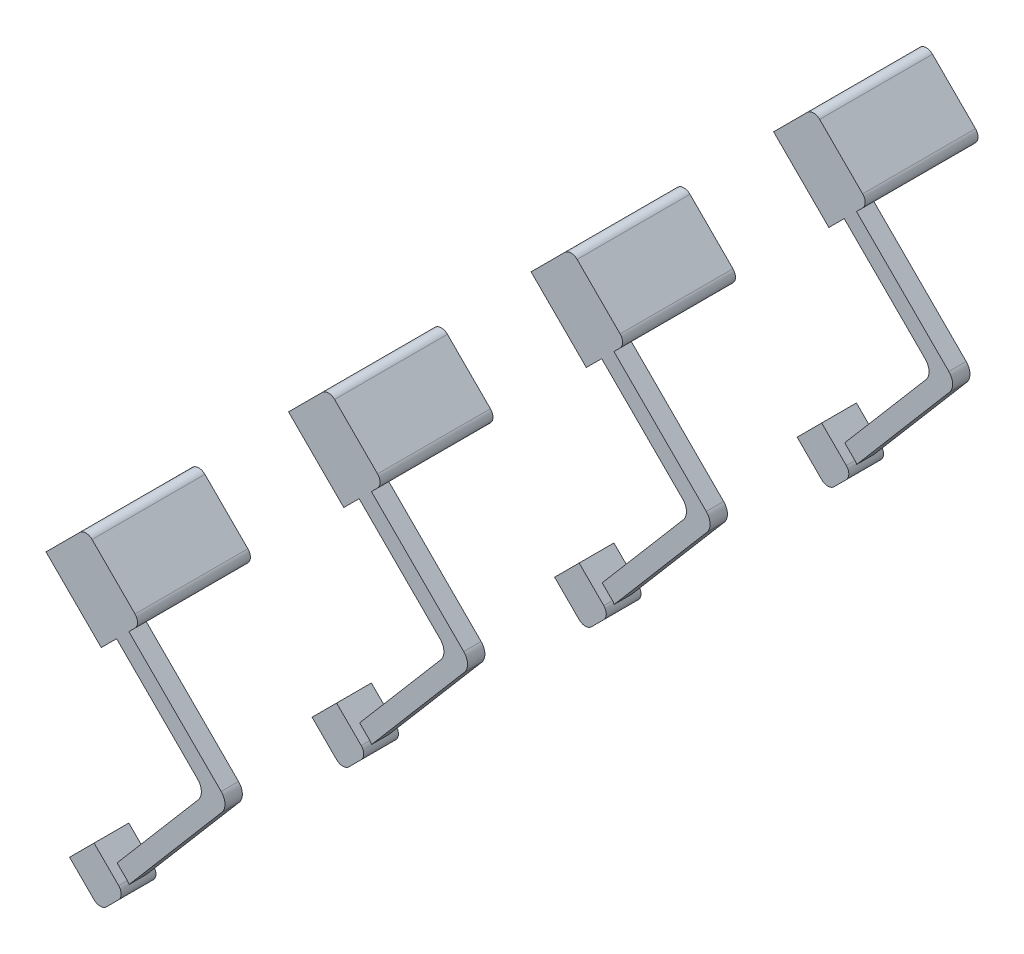
SolidWorks part; units mm, degrees
ref_plane "Front Plane" through (0, 0, 0) normal (0, 0, 1) x (1, 0, 0)
ref_plane "Top Plane" through (0, 0, 0) normal (0, 1, 0) x (1, 0, 0)
ref_plane "Right Plane" through (0, 0, 0) normal (1, 0, 0) x (0, 0, -1)
other "Configuration Table"
sketch "Sketch1" plane through (0, 0, 0) normal (0, 0, 1) x (1, 0, 0)
  line L0 (261.5942, 287.05) -> (287.05, 261.5942)
  line L1 (287.05, 261.5942) -> (302.6063, 277.1505)
  line L2 (302.6063, 282.8074) -> (282.8074, 302.6063)
  line L3 (277.1505, 302.6063) -> (261.5942, 287.05)
  arc A0 (302.6063, 277.1505) -> (302.6063, 282.8074) centre (299.7779, 279.9789) ccw
  arc A1 (282.8074, 302.6063) -> (277.1505, 302.6063) centre (279.9789, 299.7779) ccw
extrude "Coil 1" add sketch "Sketch1" along normal blind 52 from offset 4.1
sketch "Sketch2" plane through (0, 0, 0) normal (0, 0, 1) x (1, 0, 0)
  line L0 (288.4642, 274.3221) -> (331.4337, 231.3526)
  line L1 (331.7585, 223.2191) -> (288.9548, 172.9712)
  line L2 (288.9548, 172.9712) -> (295.0447, 167.7835)
  line L3 (295.0447, 167.7835) -> (342.6378, 223.6536)
  line L4 (342.3129, 231.7871) -> (294.1211, 279.9789)
  line L5 (294.1211, 279.9789) -> (288.4642, 274.3221)
  arc A0 (331.4337, 231.3526) -> (331.7585, 223.2191) centre (327.1911, 227.1099) cw
  arc A1 (342.6378, 223.6536) -> (342.3129, 231.7871) centre (338.0703, 227.5444) ccw
extrude "Plug Lead 1" add sketch "Sketch2" along normal blind 8 from offset 39.9
sketch "Sketch3" plane through (0, 0, 0) normal (0, 0, 1) x (1, 0, 0)
  line L0 (276.4434, 174.62) -> (287.7571, 163.3063)
  line L1 (293.414, 163.3063) -> (299.0708, 168.9632)
  line L2 (299.0708, 174.62) -> (287.7571, 185.9337)
  line L3 (287.7571, 185.9337) -> (276.4434, 174.62)
  arc A0 (287.7571, 163.3063) -> (293.414, 163.3063) centre (290.5855, 166.1347) ccw
  arc A1 (299.0708, 168.9632) -> (299.0708, 174.62) centre (296.2424, 171.7916) ccw
extrude "Plug Boot 1" add sketch "Sketch3" along normal blind 16 from offset 35.9
sketch "Sketch4" plane through (0, 0, 0) normal (0, 0, 1) x (1, 0, 0)
  line L0 (261.5942, 287.05) -> (287.05, 261.5942)
  line L1 (287.05, 261.5942) -> (302.6063, 277.1505)
  line L2 (302.6063, 282.8074) -> (282.8074, 302.6063)
  line L3 (277.1505, 302.6063) -> (261.5942, 287.05)
  arc A0 (302.6063, 277.1505) -> (302.6063, 282.8074) centre (299.7779, 279.9789) ccw
  arc A1 (282.8074, 302.6063) -> (277.1505, 302.6063) centre (279.9789, 299.7779) ccw
extrude "Coil 3" add sketch "Sketch4" along normal blind 52 from offset 115.86
sketch "Sketch5" plane through (0, 0, 0) normal (0, 0, 1) x (1, 0, 0)
  line L0 (288.4642, 274.3221) -> (331.4337, 231.3526)
  line L1 (331.7585, 223.2191) -> (288.9548, 172.9712)
  line L2 (288.9548, 172.9712) -> (295.0447, 167.7835)
  line L3 (295.0447, 167.7835) -> (342.6378, 223.6536)
  line L4 (342.3129, 231.7871) -> (294.1211, 279.9789)
  line L5 (294.1211, 279.9789) -> (288.4642, 274.3221)
  arc A0 (331.4337, 231.3526) -> (331.7585, 223.2191) centre (327.1911, 227.1099) cw
  arc A1 (342.6378, 223.6536) -> (342.3129, 231.7871) centre (338.0703, 227.5444) ccw
extrude "Plug Lead 3" add sketch "Sketch5" along normal blind 8 from offset 71.86
sketch "Sketch6" plane through (0, 0, 0) normal (0, 0, 1) x (1, 0, 0)
  line L0 (276.4434, 174.62) -> (287.7571, 163.3063)
  line L1 (293.414, 163.3063) -> (299.0708, 168.9632)
  line L2 (299.0708, 174.62) -> (287.7571, 185.9337)
  line L3 (287.7571, 185.9337) -> (276.4434, 174.62)
  arc A0 (287.7571, 163.3063) -> (293.414, 163.3063) centre (290.5855, 166.1347) ccw
  arc A1 (299.0708, 168.9632) -> (299.0708, 174.62) centre (296.2424, 171.7916) ccw
extrude "Plug Boot 3" add sketch "Sketch6" along normal blind 16 from offset 75.86
sketch "Sketch7" plane through (0, 0, 0) normal (0, 0, 1) x (1, 0, 0)
  line L0 (261.5942, 287.05) -> (287.05, 261.5942)
  line L1 (287.05, 261.5942) -> (302.6063, 277.1505)
  line L2 (302.6063, 282.8074) -> (282.8074, 302.6063)
  line L3 (277.1505, 302.6063) -> (261.5942, 287.05)
  arc A0 (302.6063, 277.1505) -> (302.6063, 282.8074) centre (299.7779, 279.9789) ccw
  arc A1 (282.8074, 302.6063) -> (277.1505, 302.6063) centre (279.9789, 299.7779) ccw
extrude "Coil 5" add sketch "Sketch7" along normal blind 52 from offset 227.62
sketch "Sketch8" plane through (0, 0, 0) normal (0, 0, 1) x (1, 0, 0)
  line L0 (288.4642, 274.3221) -> (331.4337, 231.3526)
  line L1 (331.7585, 223.2191) -> (288.9548, 172.9712)
  line L2 (288.9548, 172.9712) -> (295.0447, 167.7835)
  line L3 (295.0447, 167.7835) -> (342.6378, 223.6536)
  line L4 (342.3129, 231.7871) -> (294.1211, 279.9789)
  line L5 (294.1211, 279.9789) -> (288.4642, 274.3221)
  arc A0 (331.4337, 231.3526) -> (331.7585, 223.2191) centre (327.1911, 227.1099) cw
  arc A1 (342.6378, 223.6536) -> (342.3129, 231.7871) centre (338.0703, 227.5444) ccw
extrude "Plug Lead 5" add sketch "Sketch8" along normal blind 8 from offset 183.62
sketch "Sketch9" plane through (0, 0, 0) normal (0, 0, 1) x (1, 0, 0)
  line L0 (276.4434, 174.62) -> (287.7571, 163.3063)
  line L1 (293.414, 163.3063) -> (299.0708, 168.9632)
  line L2 (299.0708, 174.62) -> (287.7571, 185.9337)
  line L3 (287.7571, 185.9337) -> (276.4434, 174.62)
  arc A0 (287.7571, 163.3063) -> (293.414, 163.3063) centre (290.5855, 166.1347) ccw
  arc A1 (299.0708, 168.9632) -> (299.0708, 174.62) centre (296.2424, 171.7916) ccw
extrude "Plug Boot 5" add sketch "Sketch9" along normal blind 16 from offset 187.62
sketch "Sketch10" plane through (0, 0, 0) normal (0, 0, 1) x (1, 0, 0)
  line L0 (261.5942, 287.05) -> (287.05, 261.5942)
  line L1 (287.05, 261.5942) -> (302.6063, 277.1505)
  line L2 (302.6063, 282.8074) -> (282.8074, 302.6063)
  line L3 (277.1505, 302.6063) -> (261.5942, 287.05)
  arc A0 (302.6063, 277.1505) -> (302.6063, 282.8074) centre (299.7779, 279.9789) ccw
  arc A1 (282.8074, 302.6063) -> (277.1505, 302.6063) centre (279.9789, 299.7779) ccw
extrude "Coil 7" add sketch "Sketch10" along normal blind 52 from offset 339.38
sketch "Sketch11" plane through (0, 0, 0) normal (0, 0, 1) x (1, 0, 0)
  line L0 (288.4642, 274.3221) -> (331.4337, 231.3526)
  line L1 (331.7585, 223.2191) -> (288.9548, 172.9712)
  line L2 (288.9548, 172.9712) -> (295.0447, 167.7835)
  line L3 (295.0447, 167.7835) -> (342.6378, 223.6536)
  line L4 (342.3129, 231.7871) -> (294.1211, 279.9789)
  line L5 (294.1211, 279.9789) -> (288.4642, 274.3221)
  arc A0 (331.4337, 231.3526) -> (331.7585, 223.2191) centre (327.1911, 227.1099) cw
  arc A1 (342.6378, 223.6536) -> (342.3129, 231.7871) centre (338.0703, 227.5444) ccw
extrude "Plug Lead 7" add sketch "Sketch11" along normal blind 8 from offset 295.38
sketch "Sketch12" plane through (0, 0, 0) normal (0, 0, 1) x (1, 0, 0)
  line L0 (276.4434, 174.62) -> (287.7571, 163.3063)
  line L1 (293.414, 163.3063) -> (299.0708, 168.9632)
  line L2 (299.0708, 174.62) -> (287.7571, 185.9337)
  line L3 (287.7571, 185.9337) -> (276.4434, 174.62)
  arc A0 (287.7571, 163.3063) -> (293.414, 163.3063) centre (290.5855, 166.1347) ccw
  arc A1 (299.0708, 168.9632) -> (299.0708, 174.62) centre (296.2424, 171.7916) ccw
extrude "Plug Boot 7" add sketch "Sketch12" along normal blind 16 from offset 299.38
